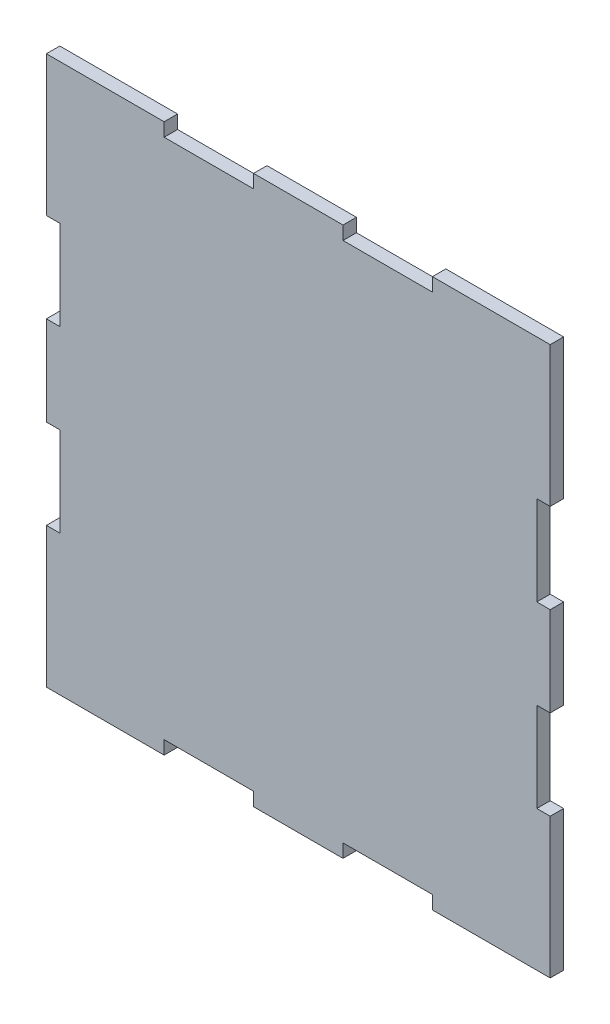
SolidWorks part; units mm, degrees
ref_plane "Front Plane" through (0, 0, 0) normal (0, 0, 1) x (1, 0, 0)
ref_plane "Top Plane" through (0, 0, 0) normal (0, 1, 0) x (1, 0, 0)
ref_plane "Right Plane" through (0, 0, 0) normal (1, 0, 0) x (0, 0, -1)
sketch "Sketch1" plane through (0, 0, 0) normal (0, 0, 1) x (1, 0, 0)
  line L0 (-9, 89.84) -> (-9, 149.84)
  line L2 (-18, -4.16) -> (-18, 89.84)
  line L4 (320, -4.16) -> (320, 89.84)
  line L5 (-9, 363.84) -> (61, 363.84)
  line L6 (311, 89.84) -> (311, 149.84)
  line L7 (-9, -4.16) -> (61, -4.16)
  line L8 (151, 355.5) -> (151, 0) construction
  line L9 (121, -4.16) -> (121, 4.84)
  line L10 (181, -4.16) -> (181, 4.84)
  line L11 (61, -4.16) -> (61, 4.84)
  line L12 (241, -4.16) -> (241, 4.84)
  line L13 (5.5, 179.84) -> (314.5, 179.84) construction
  line L14 (241, 363.84) -> (241, 354.84)
  line L15 (181, 363.84) -> (181, 354.84)
  line L16 (61, 363.84) -> (61, 354.84)
  line L17 (121, 363.84) -> (121, 354.84)
  line L18 (-18, 269.84) -> (-9, 269.84)
  line L19 (-9, 269.84) -> (-9, 209.84)
  line L20 (-9, 209.84) -> (-18, 209.84)
  line L21 (-9, 149.84) -> (-18, 149.84)
  line L22 (-18, 89.84) -> (-9, 89.84)
  line L23 (320, 89.84) -> (311, 89.84)
  line L24 (311, 149.84) -> (320, 149.84)
  line L25 (311, 209.84) -> (320, 209.84)
  line L26 (311, 269.84) -> (311, 209.84)
  line L27 (320, 269.84) -> (311, 269.84)
  line L28 (-18, -4.16) -> (-9, -4.16)
  line L30 (-9, 363.84) -> (-18, 363.84)
  line L32 (311, 363.84) -> (320, 363.84)
  line L33 (311, -4.16) -> (311, 363.84) construction
  line L34 (311, -4.16) -> (320, -4.16)
  line L36 (320, -13.16) -> (320, 372.84) construction
  line L37 (61, 354.84) -> (121, 354.84)
  line L38 (-18, 372.84) -> (320, 372.84) construction
  line L39 (181, 354.84) -> (241, 354.84)
  line L40 (121, 363.84) -> (181, 363.84)
  line L41 (-9, 363.84) -> (311, 363.84) construction
  line L42 (241, 363.84) -> (311, 363.84)
  line L44 (61, 4.84) -> (121, 4.84)
  line L45 (-18, -13.16) -> (320, -13.16) construction
  line L46 (121, -4.16) -> (181, -4.16)
  line L47 (-9, -4.16) -> (311, -4.16) construction
  line L48 (181, 4.84) -> (241, 4.84)
  line L49 (241, -4.16) -> (311, -4.16)
  line L50 (320, 149.84) -> (320, 209.84)
  line L51 (-9, -4.16) -> (-9, 363.84) construction
  line L52 (-18, 149.84) -> (-18, 209.84)
  line L53 (-18, -13.16) -> (-18, 372.84) construction
  line L54 (-9, 209.84) -> (-9, 269.84)
  line L55 (-18, 269.84) -> (-18, 363.84)
  line L56 (311, 209.84) -> (311, 269.84)
  line L57 (320, 269.84) -> (320, 363.84)
  dimension "D1" = 320
  dimension "D2" = 350
  dimension "D4" = 60
  dimension "D5" = 30
  dimension "D6" = 60
  dimension "D7" = 30
  dimension "D8" = 9
  dimension "D3" = 9
extrude "Boss-Extrude1" add sketch "Sketch1" along normal blind 9 contours L27 L57 L32 L42 L14 L39 L15 L40 L17 L37 L16 L5 L30 L55 L18 L19 L20 L52 L21 L0 L22 L2 L28 L7 L11 L44 L9 L46 L10 L48 L12 L49 L34 L4 L23 L6 L24 L50 L25 L26
